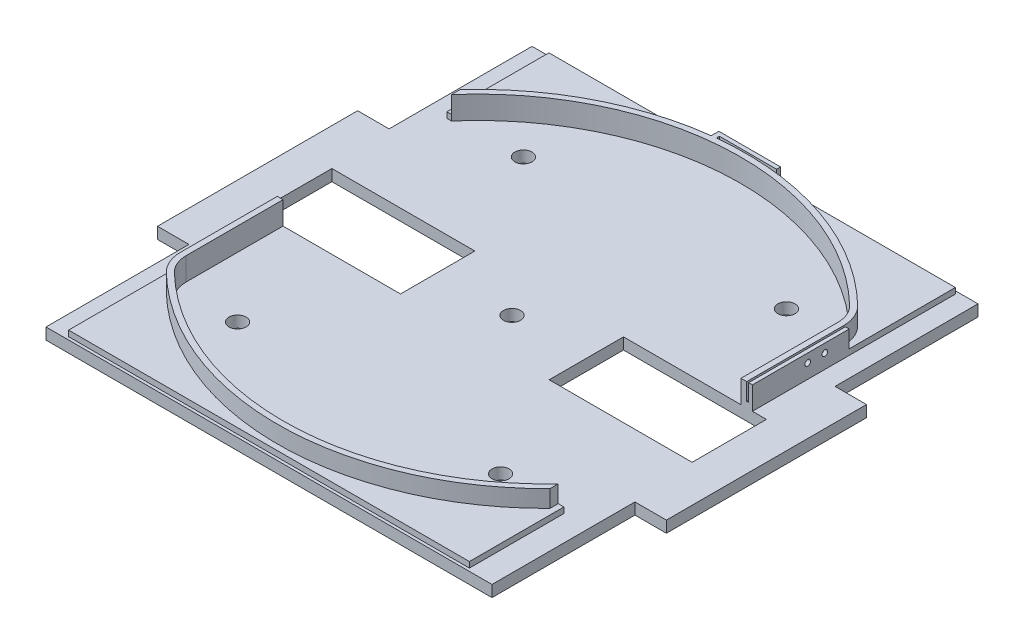
SolidWorks part; units mm, degrees
material "HDRM_Custom"
ref_plane "Front Plane" through (0, 0, 0) normal (0, 0, 1) x (1, 0, 0)
ref_plane "Top Plane" through (0, 0, 0) normal (0, 1, 0) x (1, 0, 0)
ref_plane "Right Plane" through (0, 0, 0) normal (1, 0, 0) x (0, 0, -1)
sketch "Sketch1" plane through (0, 0, 0) normal (0, 1, 0) x (1, 0, 0)
  line L0 (17.5, 42.5) -> (-39, 42.5)
  line L1 (39, -42.5) -> (17.5, -42.5)
  line L2 (39, -42.5) -> (39, -17.5)
  line L3 (39, 42.5) -> (17.5, 42.5)
  line L4 (-39, -42.5) -> (-39, -17.5)
  line L5 (39, -42.5) -> (-39, 42.5) construction
  line L6 (39, 42.5) -> (-39, -42.5) construction
  line L7 (17.5, -42.5) -> (-39, -42.5)
  line L8 (39, 17.5) -> (39, 42.5)
  line L9 (39, -17.5) -> (44.5, -17.5)
  line L10 (-39, 17.5) -> (-39, 42.5)
  line L11 (39, 17.5) -> (44.5, 17.5)
  line L12 (44.5, -17.5) -> (44.5, 17.5)
  line L13 (-39, -17.5) -> (-44.5, -17.5)
  line L15 (-39, 17.5) -> (-44.5, 17.5)
  line L16 (-44.5, -17.5) -> (-44.5, 17.5)
  point P0 (0, 0)
  dimension "D1" = 78
  dimension "D2" = 85
  dimension "D3" = 35
  dimension "D4" = 17.5
  dimension "D5" = 5.5
  dimension "D6" = 5.5
  dimension "D7" = 35
  dimension "D8" = 17.5
extrude "Boss-Extrude1" add sketch "Sketch1" along normal blind 2
sketch "Sketch2" plane through (0, 2, 0) normal (0, 1, 0) x (1, 0, 0)
  line L0 (39, 42.5) -> (-39, 42.5) construction
  line L1 (39, -42.5) -> (39, -17.5) construction
  line L2 (39, -42.5) -> (39, -17.5) construction
  line L3 (0, 42.5) -> (0, -42.5) construction
  line L5 (-44.5, 0) -> (44.5, 0) construction
  line L6 (34.5463, 23.4297) -> (34.5463, 0)
  line L7 (-34.7448, 24.1463) -> (-34.7448, 25.6512)
  line L8 (-44.5, 17.5) -> (-44.5, -17.5) construction
  line L9 (44.5, -17.5) -> (44.5, 17.5) construction
  line L10 (33.55, -26.915) -> (33.55, -25.4706)
  line L11 (-34.55, 0) -> (-34.55, -23.4261)
  line L12 (-39, -17.5) -> (-39, -42.5) construction
  line L13 (-34.55, 0) -> (-33.55, 0)
  line L14 (-33.55, 0) -> (-33.55, -23.4261)
  line L18 (34.5463, 0) -> (33.5463, 0)
  line L19 (33.5463, 0) -> (33.5463, 23.4297)
  arc A0 (-34.7448, 24.1463) -> (32.0276, 27.0187) centre (0, -6) cw
  arc A1 (-34.7448, 25.6512) -> (32.7238, 27.7365) centre (0, -6) cw
  arc A2 (-32.0317, -27.0147) -> (33.55, -25.4706) centre (0, 6) ccw
  arc A3 (-32.728, -27.7324) -> (33.55, -26.915) centre (0, 6) ccw
  arc A4 (-29.3211, 30.7325) -> (35.0118, 25.3556) centre (0, -6) cw construction
  arc A5 (34.5463, 23.4297) -> (32.7238, 27.7365) centre (28.5463, 23.4297) ccw
  arc A6 (-28.6972, 29.9509) -> (34.2668, 24.6885) centre (0, -6) cw construction
  arc A7 (33.5463, 23.4297) -> (32.0276, 27.0187) centre (28.5463, 23.4297) ccw
  arc A8 (-32.728, -27.7324) -> (-34.55, -23.4261) centre (-28.55, -23.4261) cw
  arc A9 (-32.0317, -27.0147) -> (-33.55, -23.4261) centre (-28.55, -23.4261) cw
  point P38 (34.7448, 25.6512)
  point P44 (33.5463, 25.4745)
  dimension "D1" = 46
  dimension "D9" = 6
  dimension "D11" = 5
  dimension "D12" = 5
  dimension "D3" = 4.4537
  dimension "D10" = 6
  dimension "D7" = 4.45
  dimension "D8" = 1
  dimension "D6" = 46
  dimension "D2" = 1
  dimension "D4" = 6
  dimension "D13" = 5.45
  dimension "D5" = 1
extrude "Boss-Extrude2" add sketch "Sketch2" along normal blind 4
sketch "Sketch3" plane through (0, 2, 0) normal (0, 1, 0) x (1, 0, 0)
  line L0 (34.5463, 0) -> (34.5463, 23.4297) construction
  line L1 (-35.5463, 42) -> (35.5463, 42)
  line L2 (34.5463, 0) -> (34.5463, 23.447)
  line L3 (0, 0) -> (13.3674, 0) construction
  line L4 (-34.7448, 25.6512) -> (-34.7448, 24.1463)
  line L5 (-35.55, -42) -> (34.55, -42)
  line L6 (33.55, -26.915) -> (33.55, -25.4706)
  line L7 (-34.7448, 25.6512) -> (-34.7448, 24.1463) construction
  line L9 (-34.55, -23.4261) -> (-34.55, 0)
  line L10 (-34.55, 0) -> (-35.55, 0)
  line L11 (-35.55, 0) -> (-35.55, -42)
  line L12 (34.55, -25.4706) -> (34.55, -42)
  line L13 (-35.5463, 25.9149) -> (-35.5463, 42)
  line L14 (-35.5463, 25.9149) -> (-35.5463, 24.1463)
  line L15 (-35.5463, 24.1463) -> (-34.7448, 24.1463)
  line L22 (-34.7448, 25.6512) -> (-34.7448, 24.1463) construction
  line L23 (35.5463, 0) -> (35.5463, 42)
  line L24 (34.5463, 0) -> (35.5463, 0)
  line L27 (33.55, -25.4706) -> (34.55, -25.4706)
  line L28 (39, 42.5) -> (-39, 42.5) construction
  line L29 (-39, -42.5) -> (39, -42.5) construction
  arc A0 (-34.7448, 25.6512) -> (32.7238, 27.7365) centre (0.0059, -6.1894) cw
  arc A1 (33.55, -26.915) -> (-32.728, -27.7324) centre (0, 6) cw
  arc A2 (34.5463, 23.4297) -> (32.7238, 27.7365) centre (28.5463, 23.4297) ccw construction
  arc A3 (32.0276, 27.0187) -> (-34.7448, 24.1463) centre (0, -6) ccw construction
  arc A4 (32.7238, 27.7365) -> (34.5463, 23.447) centre (28.587, 23.447) cw
  arc A5 (32.7238, 27.7365) -> (-34.7448, 25.6512) centre (0, -6) ccw construction
  arc A9 (-32.728, -27.7324) -> (-34.55, -23.4261) centre (-28.55, -23.4261) cw
  dimension "D1" = 1
  dimension "D2" = 1
  dimension "D3" = 1
  dimension "D4" = 0.5
  dimension "D5" = 0.5
extrude "Boss-Extrude3" add sketch "Sketch3" along normal blind 1
sketch "Sketch4" plane through (0, 3, 0) normal (0, 1, 0) x (1, 0, 0)
  line L1 (-5.8, 41.9776) -> (5, 41.9776)
  line L3 (-5, 41.2776) -> (5, 41.2776)
  line L4 (5, 41.9776) -> (5, 41.2776)
  line L9 (-5, 41.2776) -> (-5, 40.0776)
  line L10 (-5, 40.0776) -> (-5.8, 40.0776)
  line L11 (-5.8, 41.9776) -> (-5.8, 40.0776)
  arc A0 (32.7238, 27.7365) -> (-34.7448, 25.6512) centre (0, -6) ccw construction
  point P6 (-1.4519, 40.9776)
  dimension "D1" = 0.3
  dimension "D2" = 10
  dimension "D3" = 0.7
  dimension "D4" = 0.8
  dimension "D6" = 1.2
extrude "Boss-Extrude4" add sketch "Sketch4" along normal blind 3
sketch "Sketch7" plane through (0, 0, 0) normal (0, -1, 0) x (1, 0, 0)
  line L1 (6.5, -38) -> (-6.5, -38)
  line L2 (6.5, -38) -> (6.5, -13)
  line L3 (6.5, -13) -> (-6.5, -13)
  line L4 (-6.5, -38) -> (-6.5, -13)
  line L5 (6.5, 13) -> (-6.5, 13)
  line L6 (6.5, 13) -> (6.5, 38)
  line L7 (6.5, 38) -> (-6.5, 38)
  line L8 (-6.5, 13) -> (-6.5, 38)
extrude "Cut-Extrude2" cut sketch "Sketch7" against normal blind 0.75
hole_wizard "Ø3.0 (3) Diameter Hole1" positions "Sketch11" profile "Sketch10" hole size "Ø3.0" standard "ISO" end condition through all
sketch "Sketch11" plane through (0, 2, 0) normal (0, 1, 0) x (1, 0, 0)
  point P0 (-23, 25)
  point P2 (-23, -25)
  point P4 (23, -25)
  point P6 (23, 25)
  point P8 (0, 0)
  dimension "D1" = 25
  dimension "D2" = 23
  dimension "D3" = 23
  dimension "D4" = 25
  dimension "D5" = 50
  dimension "D6" = 23
  dimension "D7" = 25
  dimension "D8" = 46
sketch "Sketch10" plane through (-23, 2, -25) normal (1, 0, 0) x (0, 0, 1)
  line L0 (0, 0) -> (0, 2)
  line L1 (0, 2) -> (1.5, 2)
  line L2 (1.5, 2) -> (1.5, 0)
  line L5 (1.5, 0) -> (0, 0)
  line L11 (0, -6.35) -> (0, 107.95) construction
  dimension "Thru Hole Dia." = 3
  dimension "Thru Hole Depth" = 2
hole_wizard "Ø1.0 (1) Diameter Hole1" positions "Sketch14" profile "Sketch12" hole size "Ø1.0" standard "ISO"
sketch "Sketch14" plane through (0, 0, -41.2776) normal (0, 0, 1) x (1, 0, 0)
  line L2 (-5, 6) -> (-5, 3) construction
  line L3 (-5, 6) -> (5, 6) construction
  point P0 (-3.7, 4.5)
  point P2 (-1.7, 4.5)
  dimension "D1" = 1.5
  dimension "D2" = 1.3
  dimension "D3" = 1.5
  dimension "D4" = 2
sketch "Sketch12" plane through (-3.7, 4.5, -41.2776) normal (1, 0, 0) x (0, -1, 0)
  line L0 (0, 0) -> (0, 1.2224)
  line L1 (0, 1.2224) -> (0.5, 1.2224)
  line L2 (0.5, 1.2224) -> (0.5, 0)
  line L5 (0.5, 0) -> (0, 0)
  line L11 (0, -6.35) -> (0, 107.95) construction
  dimension "Thru Hole Dia." = 1
  dimension "Thru Hole Depth" = 1.2224
hole_wizard "Ø1.0 (1) Diameter Hole2" positions "Sketch17" profile "Sketch15" hole size "Ø1.0" standard "ISO"
sketch "Sketch17" plane through (33.5463, 0, 0) normal (-1, 0, 0) x (0, 0, 1)
  line L0 (-23.4297, 6) -> (0, 6) construction
  line L2 (-23.4297, 6) -> (-23.4297, 2) construction
  point P0 (-19.1697, 4.5)
  point P2 (-16.1697, 4.5)
  dimension "D1" = 1.5
  dimension "D2" = 1.5
  dimension "D3" = 3
  dimension "D4" = 4.26
sketch "Sketch15" plane through (33.5463, 4.5, -19.1697) normal (0, 1, 0) x (0, 0, 1)
  line L0 (0, 0) -> (0, 3)
  line L1 (0, 3) -> (0.5, 3)
  line L2 (0.5, 3) -> (0.5, 0)
  line L5 (0.5, 0) -> (0, 0)
  line L10 (0, 3) -> (-0.5, 3) construction
  line L11 (0, -6.35) -> (0, 107.95) construction
  dimension "Hole Dia." = 1
  dimension "Hole Depth" = 3
  dimension "Drill Angle" = 180
sketch "Sketch18" plane through (0, 0.75, 0) normal (0, -1, 0) x (1, 0, 0)
  line L2 (-38, -6.5) -> (-13, -6.5)
  line L3 (-38, -6.5) -> (-38, 6.5)
  line L4 (-38, 6.5) -> (-13, 6.5)
  line L7 (-13, -6.5) -> (-13, 6.5)
  line L8 (13, -6.5) -> (38, -6.5)
  line L9 (13, -6.5) -> (13, 6.5)
  line L10 (13, 6.5) -> (38, 6.5)
  line L12 (38, -6.5) -> (38, 6.5)
extrude "Cut-Extrude4" cut sketch "Sketch18" against normal blind 10
sketch "Sketch19" plane through (0, 0.75, 0) normal (0, 1, 0) x (1, 0, 0)
  line L0 (-38, -6.5) -> (-35.55, -6.5) construction
  line L1 (-38, -6.5) -> (-13, -6.5)
  line L2 (-38, -6.5) -> (-38, 6.5)
  line L3 (-38, 6.5) -> (-13, 6.5)
  line L4 (-13, -6.5) -> (-13, 6.5)
  line L5 (-13, 6.5) -> (-38, 6.5) construction
  line L6 (38, -6.5) -> (38, 6.5) construction
  line L7 (13, -6.5) -> (38, -6.5)
  line L8 (13, -6.5) -> (13, 6.5)
  line L9 (13, 6.5) -> (38, 6.5)
  line L10 (38, -6.5) -> (38, 6.5)
  line L11 (38, 6.5) -> (35.5463, 6.5) construction
extrude "Cut-Extrude5" cut sketch "Sketch19" against normal through all
sketch "Sketch20" plane through (0, 3, 0) normal (0, 1, 0) x (1, 0, 0)
  line L0 (34.5463, 6.5) -> (34.5463, 23.4297) construction
  line L1 (35.5463, 6.5) -> (34.8763, 6.5)
  line L2 (35.5463, 6.5) -> (35.5463, 23.4297)
  line L3 (35.5463, 23.4297) -> (34.8763, 23.4297)
  line L4 (34.8763, 6.5) -> (34.8763, 23.4297)
  dimension "D1" = 0.33
extrude "Boss-Extrude5" add sketch "Sketch20" along normal blind 3
hole_wizard "Ø1.0 (1) Diameter Hole3" positions "Sketch22" profile "Sketch21" hole size "Ø1.0" standard "ISO"
sketch "Sketch22" plane through (34.8763, 0, 0) normal (-1, 0, 0) x (0, 0, 1)
  point P0 (-19.1697, 4.5)
  point P2 (-16.1697, 4.5)
sketch "Sketch21" plane through (34.8763, 4.5, -19.1697) normal (0, 1, 0) x (0, 0, 1)
  line L0 (0, 0) -> (0, 3)
  line L1 (0, 3) -> (0.5, 3)
  line L2 (0.5, 3) -> (0.5, 0)
  line L5 (0.5, 0) -> (0, 0)
  line L10 (0, 3) -> (-0.5, 3) construction
  line L11 (0, -6.35) -> (0, 107.95) construction
  dimension "Hole Dia." = 1
  dimension "Hole Depth" = 3
  dimension "Drill Angle" = 180
